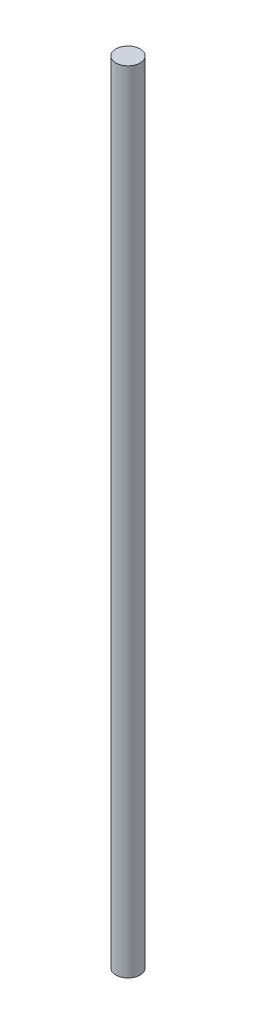
SolidWorks part; units mm, degrees
ref_plane "Front Plane" through (0, 0, 0) normal (0, 0, 1) x (1, 0, 0)
ref_plane "Top Plane" through (0, 0, 0) normal (0, 1, 0) x (1, 0, 0)
ref_plane "Right Plane" through (0, 0, 0) normal (1, 0, 0) x (0, 0, -1)
other "Configuration Table"
sketch "Sketch1" plane through (0, 0, 0) normal (0, 1, 0) x (1, 0, 0)
  circle A0 centre (350, 400) radius 8
extrude "PACK_bilyali_vida_1605" add sketch "Sketch1" along normal blind 520 from offset 380 separate body
